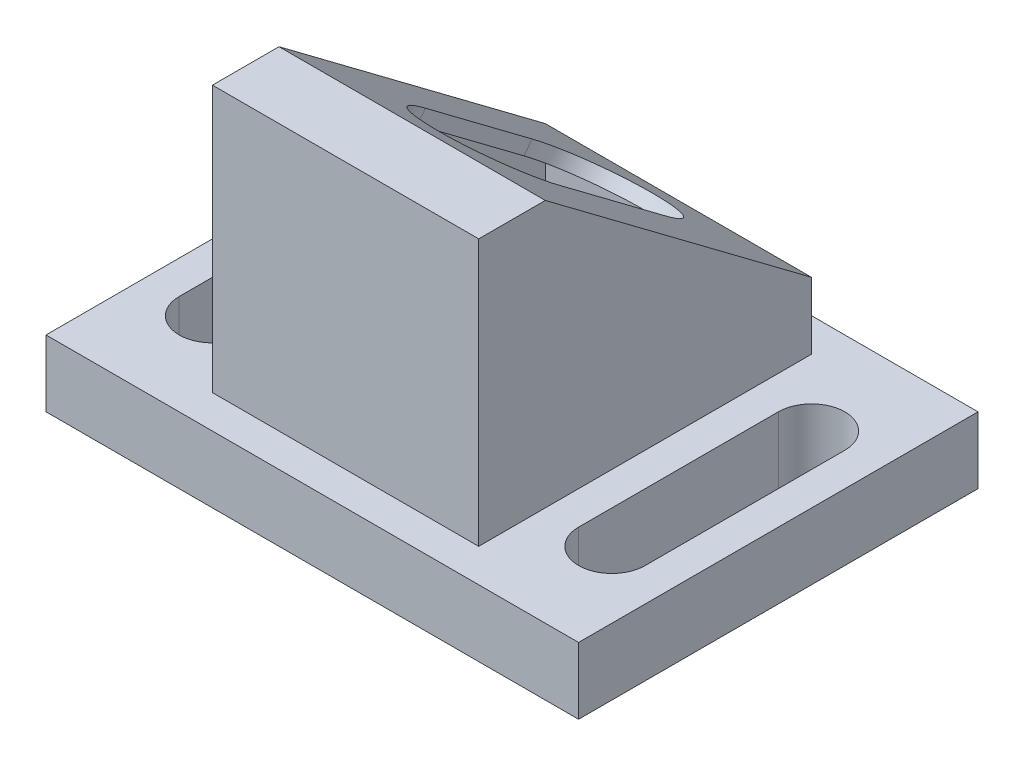
SolidWorks part; units mm, degrees
material "Titanium Ti-8Mn, Annealed"
ref_plane "Front" through (0, 0, 0) normal (0, 0, 1) x (1, 0, 0)
ref_plane "Top" through (0, 0, 0) normal (0, 1, 0) x (1, 0, 0)
ref_plane "Right" through (0, 0, 0) normal (1, 0, 0) x (0, 0, -1)
sketch "Sketch1" plane through (0, 0, 0) normal (0, 1, 0) x (1, 0, 0)
  line L1 (0, 0) -> (101.6, 0)
  line L2 (0, 0) -> (0, -76.2)
  line L3 (0, -76.2) -> (101.6, -76.2)
  line L4 (101.6, 0) -> (101.6, -76.2)
  dimension "D1" = 101.6
  dimension "D2" = 76.2
extrude "Boss-Extrude1" add sketch "Sketch1" along normal blind 12.7
ref_plane "Plane1" through (50.8, 0, 0) normal (1, 0, 0) x (0, 0, -1)
sketch "Sketch4" plane through (0, 12.7, 0) normal (0, 1, 0) x (1, 0, 0)
  line L0 (12.7, -19.05) -> (12.7, -57.15) construction
  line L1 (19.05, -19.05) -> (19.05, -57.15)
  line L2 (6.35, -19.05) -> (6.35, -57.15)
  line L3 (101.6, 0) -> (0, 0) construction
  line L4 (101.6, -76.2) -> (101.6, 0) construction
  line L5 (88.9, -19.05) -> (88.9, -57.15) construction
  line L6 (95.25, -19.05) -> (95.25, -57.15)
  line L7 (82.55, -19.05) -> (82.55, -57.15)
  line L8 (0, 0) -> (0, -76.2) construction
  arc A0 (19.05, -19.05) -> (6.35, -19.05) centre (12.7, -19.05) ccw
  arc A1 (6.35, -57.15) -> (19.05, -57.15) centre (12.7, -57.15) ccw
  arc A2 (95.25, -19.05) -> (82.55, -19.05) centre (88.9, -19.05) ccw
  arc A3 (82.55, -57.15) -> (95.25, -57.15) centre (88.9, -57.15) ccw
  point P2 (12.7, -38.1)
  point P13 (88.9, -38.1)
  dimension "D1" = 19.05
  dimension "D3" = 19.05
  dimension "D2" = 88.9
  dimension "D4" = 88.9
extrude "Cut-Extrude1" cut sketch "Sketch4" against normal blind 12.7
ref_plane "Plane2" through (50.8, 0, 0) normal (1, 0, 0) x (0, 0, -1)
sketch "Sketch5" plane through (50.8, 0, 0) normal (1, 0, 0) x (0, 0, -1)
  line L0 (0, 12.7) -> (0, 0) construction
  line L1 (-76.2, 12.7) -> (0, 12.7) construction
  line L2 (-6.35, 12.7) -> (-6.35, 25.4)
  line L3 (-69.85, 12.7) -> (-69.85, 63.5)
  line L4 (-76.2, 12.7) -> (-76.2, 0) construction
  line L5 (-69.85, 63.5) -> (-57.15, 63.5)
  line L6 (-57.15, 63.5) -> (-6.35, 25.4)
  line L7 (-69.85, 12.7) -> (-6.35, 12.7)
  dimension "D1" = 6.35
  dimension "D2" = 12.7
  dimension "D3" = 6.35
  dimension "D4" = 50.8
  dimension "D5" = 12.7
extrude "Boss-Extrude2" add sketch "Sketch5" along normal mid plane 50.8
sketch "Sketch10" plane through (0, 13.208, -9.906) normal (0, 0.8, -0.6) x (1, 0, 0)
  line L0 (50.8, -39.37) -> (50.8, -64.77) construction
  line L1 (63.5, -39.37) -> (63.5, -64.77)
  line L2 (38.1, -39.37) -> (38.1, -64.77)
  line L3 (76.2, -20.32) -> (25.4, -20.32) construction
  line L4 (25.4, -20.32) -> (25.4, -83.82) construction
  arc A0 (63.5, -39.37) -> (38.1, -39.37) centre (50.8, -39.37) ccw
  arc A1 (38.1, -64.77) -> (63.5, -64.77) centre (50.8, -64.77) ccw
  point P2 (50.8, -52.07)
  dimension "D1" = 19.05
  dimension "D2" = 25.4
extrude "Cut-Extrude3" cut sketch "Sketch10" against normal blind 12.7
ref_plane "Plane7" through (50.8, 0, 0) normal (1, 0, 0) x (0, 0, -1)
sketch "Sketch12" plane through (50.8, 0, 0) normal (1, 0, 0) x (0, 0, -1)
  line L0 (-10.16, 25.0825) -> (-56.3033, 59.69)
  line L3 (-10.16, 12.7) -> (-10.16, 25.0825)
  line L9 (-57.15, 59.69) -> (-69.85, 59.69)
  line L11 (-69.596, 12.7) -> (-10.16, 12.7)
  line L12 (-56.3033, 59.69) -> (-69.596, 59.69)
  line L13 (-69.596, 59.69) -> (-69.596, 12.7)
  dimension "D1" = 10.16
  dimension "D2" = 25.0825
  dimension "D3" = 69.596
  dimension "D4" = 12.7
  dimension "D5" = 56.3033
  dimension "D6" = 3.81
extrude "Cut-Extrude7" cut sketch "Sketch12" against normal mid plane 43.18
